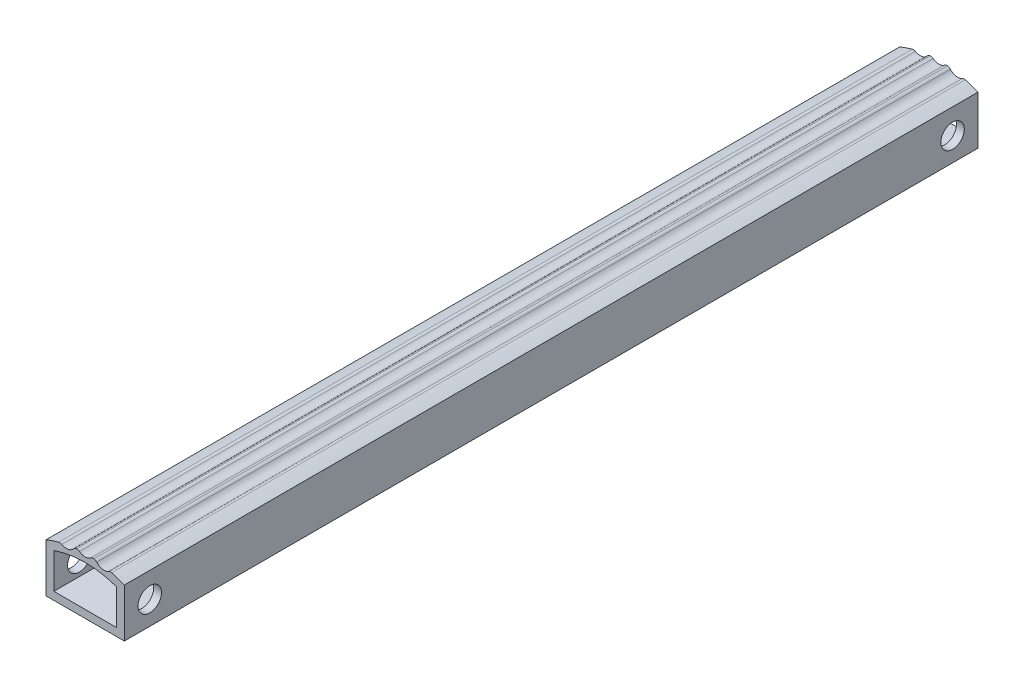
SolidWorks part; units mm, degrees
material "Alliage 1060"
ref_plane "Plan de face" through (0, 0, 0) normal (0, 0, 1) x (1, 0, 0)
ref_plane "Plan de dessus" through (0, 0, 0) normal (0, 1, 0) x (1, 0, 0)
ref_plane "Plan de droite" through (0, 0, 0) normal (1, 0, 0) x (0, 0, -1)
sketch "Esquisse1" plane through (0, 0, 0) normal (0, 0, 1) x (1, 0, 0)
  line L0 (-4, 1) -> (-4, 5.5137)
  line L1 (-5, 0) -> (5, 0)
  line L2 (-5, 0) -> (-5, 6.2)
  line L3 (4, 1) -> (4, 5.5137)
  line L4 (5, 0) -> (5, 6.2)
  line L5 (-4, 1) -> (4, 1)
  line L6 (0, 1) -> (0, 9.1925) construction
  line L7 (-0.2854, -5.8159) -> (-0.8676, 7.171) construction
  line L8 (-0.2854, -5.8159) -> (1.3964, 7.0748) construction
  arc A0 (5, 6.2) -> (3.3785, 6.7533) centre (0, -5.8) ccw
  arc A1 (4, 5.5137) -> (-4, 5.5137) centre (0, -5.8) ccw
  arc A2 (-0.7353, 7.0517) -> (0.7353, 7.0517) centre (0, 8) ccw
  arc A3 (1.4727, 6.9725) -> (2.9975, 6.7029) centre (2.3948, 7.7405) ccw
  arc A4 (-1.4727, 6.9725) -> (-2.9975, 6.7029) centre (-2.3948, 7.7405) cw
  arc A5 (-3.3785, 6.7533) -> (-5, 6.2) centre (0, -5.8) ccw
  arc A6 (-1.0833, 7.1548) -> (-1.1321, 7.1506) centre (0, -5.8) ccw
  arc A7 (5, 6.2) -> (-5, 6.2) centre (0, -5.8) ccw construction
  arc A8 (1.1321, 7.1506) -> (1.0833, 7.1548) centre (0, -5.8) ccw
  arc A9 (2.9975, 6.7029) -> (3.3785, 6.7533) centre (3.2486, 6.2705) cw
  arc A10 (1.4727, 6.9725) -> (1.1321, 7.1506) centre (1.0886, 6.6525) ccw
  arc A11 (0.7353, 7.0517) -> (1.0833, 7.1548) centre (1.0417, 6.6565) cw
  arc A12 (-0.7353, 7.0517) -> (-1.0833, 7.1548) centre (-1.0417, 6.6565) ccw
  arc A13 (-1.4727, 6.9725) -> (-1.1321, 7.1506) centre (-1.0886, 6.6525) cw
  arc A14 (-2.9975, 6.7029) -> (-3.3785, 6.7533) centre (-3.2486, 6.2705) ccw
  point P29 (1.3627, 7.1284)
  point P32 (0.8676, 7.171)
  point P35 (-0.8676, 7.171)
  point P40 (-3.1543, 6.8115)
  dimension "D5" = 1.2
  dimension "D9" = 0.5
  dimension "D1" = 10
  dimension "D2" = 5.8
  dimension "D3" = 6.2
  dimension "D6" = 2
  dimension "D7" = 7
  dimension "D8" = 10
  dimension "D4" = 1
extrude "Boss.-Extru.1" add sketch "Esquisse1" along normal mid plane 109
sketch "Esquisse2" plane through (-5, 0, 0) normal (-1, 0, 0) x (0, 0, 1)
  line L0 (54.5, 0) -> (-54.5, 0) construction
  circle A0 centre (-51.25, 3) radius 1.5
  circle A1 centre (51.25, 3) radius 1.5
  dimension "D1" = 3
  dimension "D2" = 3
  dimension "D3" = 102.5
  dimension "D4" = 51.25
  dimension "D5" = 3
extrude "Enlèv. mat.-Extru.1" cut sketch "Esquisse2" against normal through all
